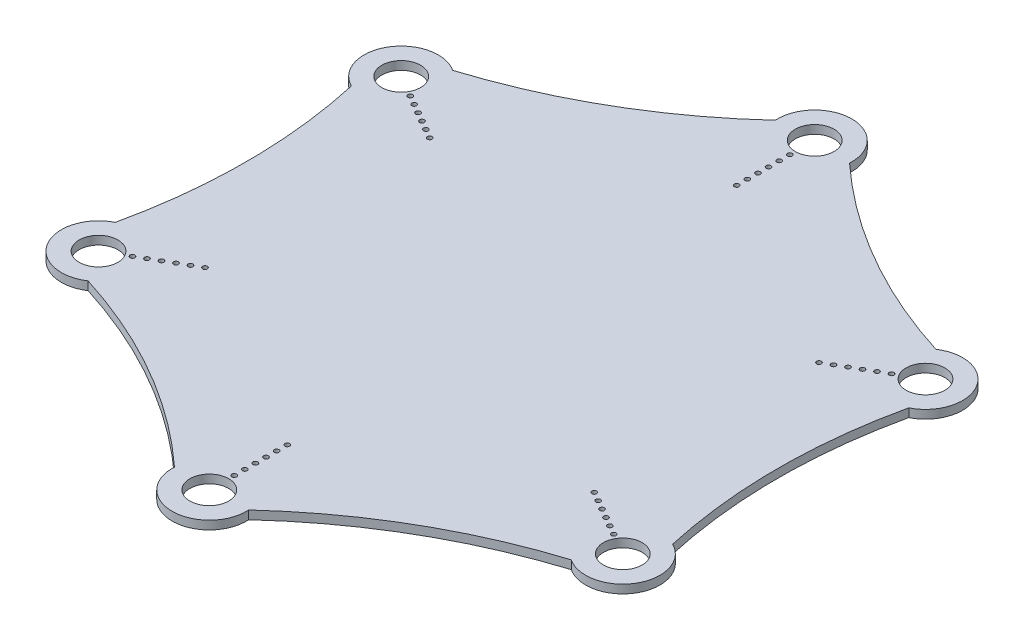
SolidWorks part; units mm, degrees
material "Fibra de Vidro A"
ref_plane "Plano frontal" through (0, 0, 0) normal (0, 0, 1) x (1, 0, 0)
ref_plane "Plano superior" through (0, 0, 0) normal (0, 1, 0) x (1, 0, 0)
ref_plane "Plano direito" through (0, 0, 0) normal (1, 0, 0) x (0, 0, -1)
sketch "Esboço1" plane through (0, 0, 0) normal (0, 1, 0) x (1, 0, 0)
  circle A0 centre (0, 0) radius 50 construction
  circle A1 centre (0, 0) radius 64 construction
  circle A2 centre (0, 57) radius 5.85 construction
  circle A3 centre (0, 57) radius 3.65
  circle A4 centre (49.3634, 28.5) radius 5.85 construction
  circle A5 centre (49.3634, 28.5) radius 3.65
  circle A6 centre (49.3634, -28.5) radius 5.85 construction
  circle A7 centre (49.3634, -28.5) radius 3.65
  circle A8 centre (0, -57) radius 5.85 construction
  circle A9 centre (0, -57) radius 3.65
  circle A10 centre (-49.3634, -28.5) radius 5.85 construction
  circle A11 centre (-49.3634, -28.5) radius 3.65
  circle A12 centre (-49.3634, 28.5) radius 5.85 construction
  circle A13 centre (-49.3634, 28.5) radius 3.65
  arc A14 (6.9868, 56.5702) -> (-6.9868, 56.5702) centre (0, 57) ccw
  arc A15 (-45.4978, 34.3358) -> (-52.4846, 22.2343) centre (-49.3634, 28.5) ccw
  circle A16 centre (0, 0) radius 57 construction
  arc A17 (-45.4978, 34.3358) -> (-6.9868, 56.5702) centre (-75.8804, 131.4288) ccw
  arc A18 (6.9868, 56.5702) -> (45.4978, 34.3358) centre (75.8804, 131.4288) ccw
  arc A19 (52.4846, 22.2343) -> (45.4978, 34.3358) centre (49.3634, 28.5) ccw
  arc A20 (52.4846, 22.2343) -> (52.4846, -22.2343) centre (151.7609, 0) ccw
  arc A21 (45.4978, -34.3358) -> (52.4846, -22.2343) centre (49.3634, -28.5) ccw
  arc A22 (45.4978, -34.3358) -> (6.9868, -56.5702) centre (75.8804, -131.4288) ccw
  arc A23 (-6.9868, -56.5702) -> (6.9868, -56.5702) centre (0, -57) ccw
  arc A24 (-6.9868, -56.5702) -> (-45.4978, -34.3358) centre (-75.8804, -131.4288) ccw
  arc A25 (-52.4846, -22.2343) -> (-45.4978, -34.3358) centre (-49.3634, -28.5) ccw
  arc A26 (-52.4846, -22.2343) -> (-52.4846, 22.2343) centre (-151.7609, 0) ccw
  arc A27 (-45.4978, 34.3358) -> (-52.4846, 22.2343) centre (-49.3634, 28.5) ccw
  dimension "D1" = 128
  dimension "D2" = 11.7
  dimension "D3" = 100
  dimension "D4" = 7.3
  dimension "D5" = 57
  dimension "D6" = 49.3634
  dimension "D7" = 6
  dimension "D8" = 114
  dimension "D9" = 101.7356
  dimension "D10" = 57
  dimension "D11" = 6
extrude "Ressalto-extrusão1" add sketch "Esboço1" along normal blind 1.6 contours A26 A25 A24 A23 A22 A21 A20 A19 A18 A14 A17 A15 A13 A11 A9 A7 A5 A3
sketch "Esboço3" plane through (0, 1.6, 0) normal (0, 1, 0) x (1, 0, 0)
  circle A0 centre (0, 0) radius 0.0001
extrude "Ressalto-extrusão3" add sketch "Esboço3" along normal blind 0.001
sketch "Esboço5" plane through (0, 1.6, 0) normal (0, 1, 0) x (1, 0, 0)
  line L0 (0, -57) -> (0, -52.32) construction
  circle A0 centre (0, -52.32) radius 0.45
  circle A1 centre (0, 0) radius 52.32 construction
  circle A2 centre (-45.3104, -26.16) radius 0.45
  circle A3 centre (-45.3104, 26.16) radius 0.45
  circle A4 centre (0, 52.32) radius 0.45
  circle A5 centre (45.3104, 26.16) radius 0.45
  circle A6 centre (45.3104, -26.16) radius 0.45
  circle A7 centre (0, -50.32) radius 0.45
  circle A8 centre (0, -48.32) radius 0.45
  circle A9 centre (0, -46.32) radius 0.45
  circle A10 centre (0, -44.32) radius 0.45
  circle A11 centre (0, -42.32) radius 0.45
  circle A12 centre (-36.6502, -21.16) radius 0.45
  circle A13 centre (-38.3822, -22.16) radius 0.45
  circle A14 centre (-40.1143, -23.16) radius 0.45
  circle A15 centre (-41.8463, -24.16) radius 0.45
  circle A16 centre (-43.5784, -25.16) radius 0.45
  circle A17 centre (-36.6502, 21.16) radius 0.45
  circle A18 centre (-38.3822, 22.16) radius 0.45
  circle A19 centre (-40.1143, 23.16) radius 0.45
  circle A20 centre (-41.8463, 24.16) radius 0.45
  circle A21 centre (-43.5784, 25.16) radius 0.45
  circle A22 centre (0, 42.32) radius 0.45
  circle A23 centre (0, 44.32) radius 0.45
  circle A24 centre (0, 46.32) radius 0.45
  circle A25 centre (0, 48.32) radius 0.45
  circle A26 centre (0, 50.32) radius 0.45
  circle A27 centre (36.6502, 21.16) radius 0.45
  circle A28 centre (38.3822, 22.16) radius 0.45
  circle A29 centre (40.1143, 23.16) radius 0.45
  circle A30 centre (41.8463, 24.16) radius 0.45
  circle A31 centre (43.5784, 25.16) radius 0.45
  circle A32 centre (36.6502, -21.16) radius 0.45
  circle A33 centre (38.3822, -22.16) radius 0.45
  circle A34 centre (40.1143, -23.16) radius 0.45
  circle A35 centre (41.8463, -24.16) radius 0.45
  circle A36 centre (43.5784, -25.16) radius 0.45
  dimension "D1" = 6
  dimension "D2" = 6
  dimension "D3" = 6
extrude "Corte-extrusão2" cut sketch "Esboço5" against normal up to next (1.6 mm away)
